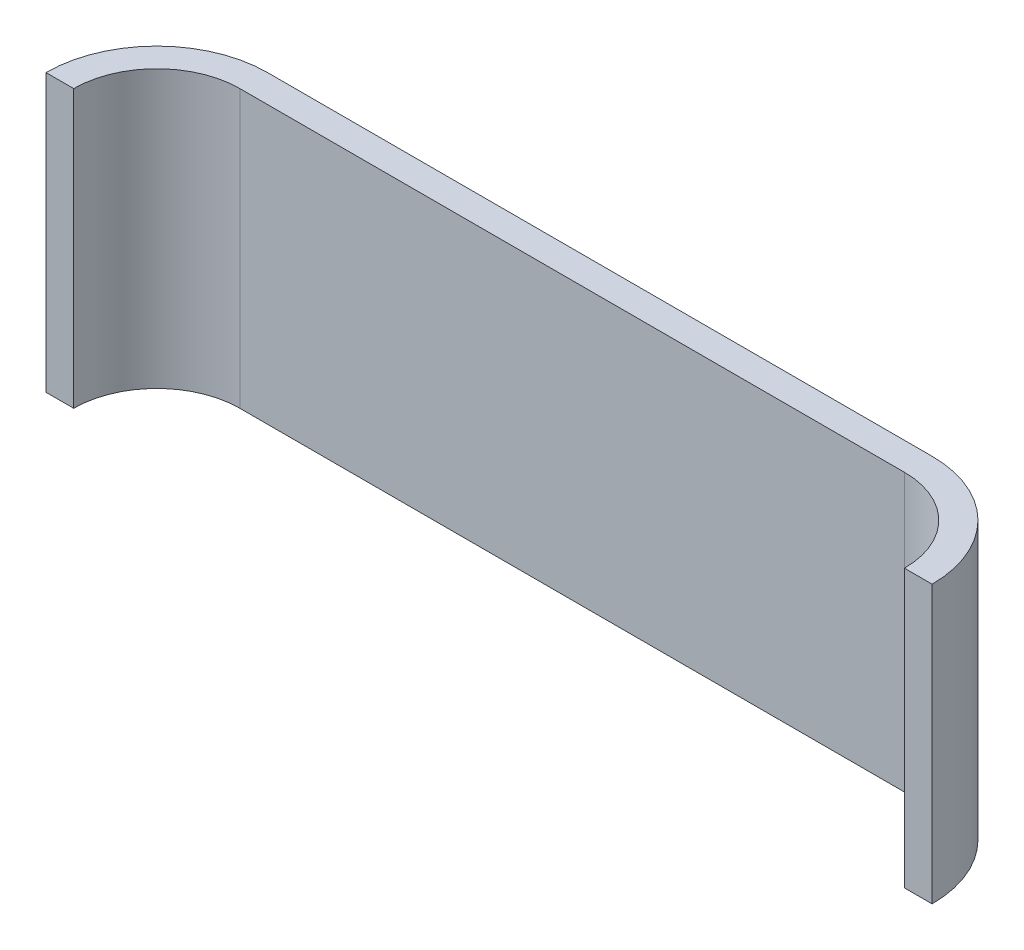
SolidWorks part; units mm, degrees
ref_plane "Front Plane" through (0, 0, 0) normal (0, 0, 1) x (1, 0, 0)
ref_plane "Top Plane" through (0, 0, 0) normal (0, 1, 0) x (1, 0, 0)
ref_plane "Right Plane" through (0, 0, 0) normal (1, 0, 0) x (0, 0, -1)
sketch "Sketch1" plane through (0, 0, 0) normal (0, 1, 0) x (1, 0, 0)
  line L0 (1500, 0) -> (13500, 0)
  line L1 (1500, 500) -> (13500, 500)
  line L2 (-500, -1500) -> (0, -1500)
  line L3 (15500, -1500) -> (15000, -1500)
  arc A0 (15000, -1500) -> (13500, 0) centre (13500, -1500) ccw
  arc A1 (1500, 0) -> (0, -1500) centre (1500, -1500) ccw
  arc A2 (1500, 500) -> (-500, -1500) centre (1500, -1500) ccw
  arc A3 (15500, -1500) -> (13500, 500) centre (13500, -1500) ccw
  point P9 (0, 0)
  dimension "D1" = 1500
  dimension "D2" = 500
extrude "Boss-Extrude1" add sketch "Sketch1" along normal blind 5000
